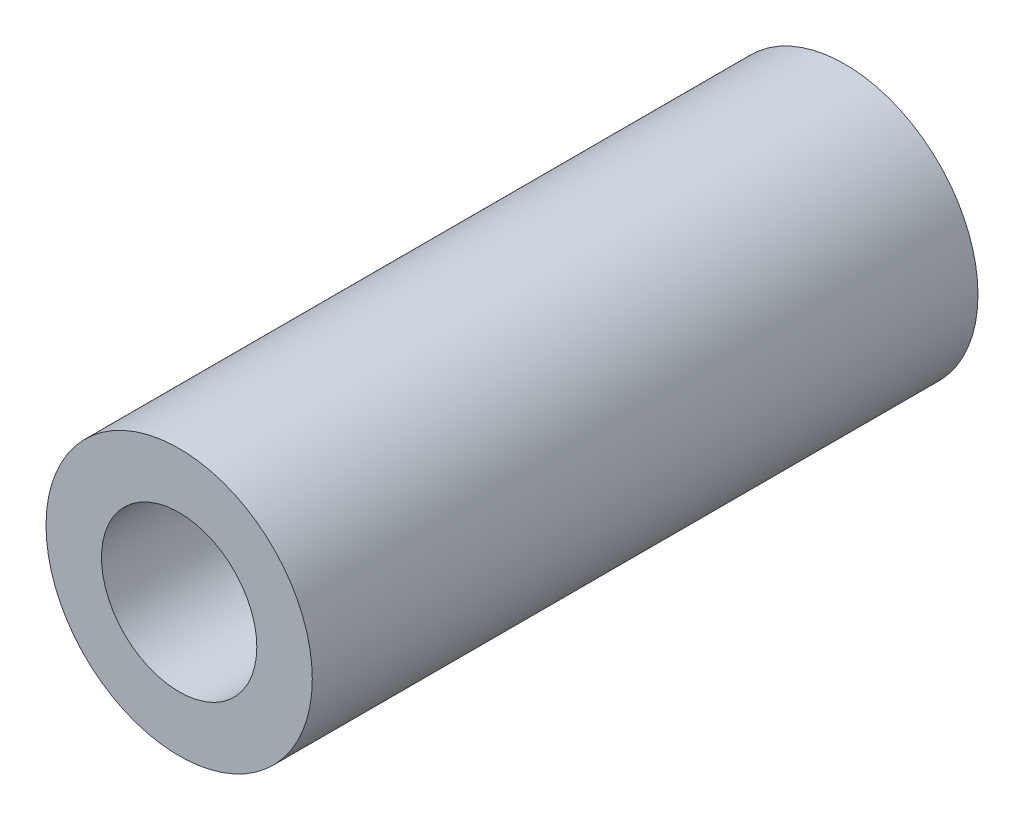
SolidWorks part; units mm, degrees
ref_plane "Front Plane" through (0, 0, 0) normal (0, 0, 1) x (1, 0, 0)
ref_plane "Top Plane" through (0, 0, 0) normal (0, 1, 0) x (1, 0, 0)
ref_plane "Right Plane" through (0, 0, 0) normal (1, 0, 0) x (0, 0, -1)
ref_plane "Plane1" through (0, 0.8065, 0) normal (0, 1, 0) x (1, 0, 0)
sketch "Sketch1" plane through (0, 0.8065, 0) normal (0, 1, 0) x (1, 0, 0)
  line L0 (3.1378, -10) -> (3.1378, 0)
  line L1 (3.1378, 0) -> (2.3045, 0)
  line L2 (2.3045, 0) -> (2.3045, -10)
  line L3 (2.3045, -10) -> (3.1378, -10)
  line L4 (1.1378, 0) -> (1.1378, -10) construction
  dimension "D1" = 10
revolve "Revolve1" add sketch "Sketch1" angle 360 about L4
